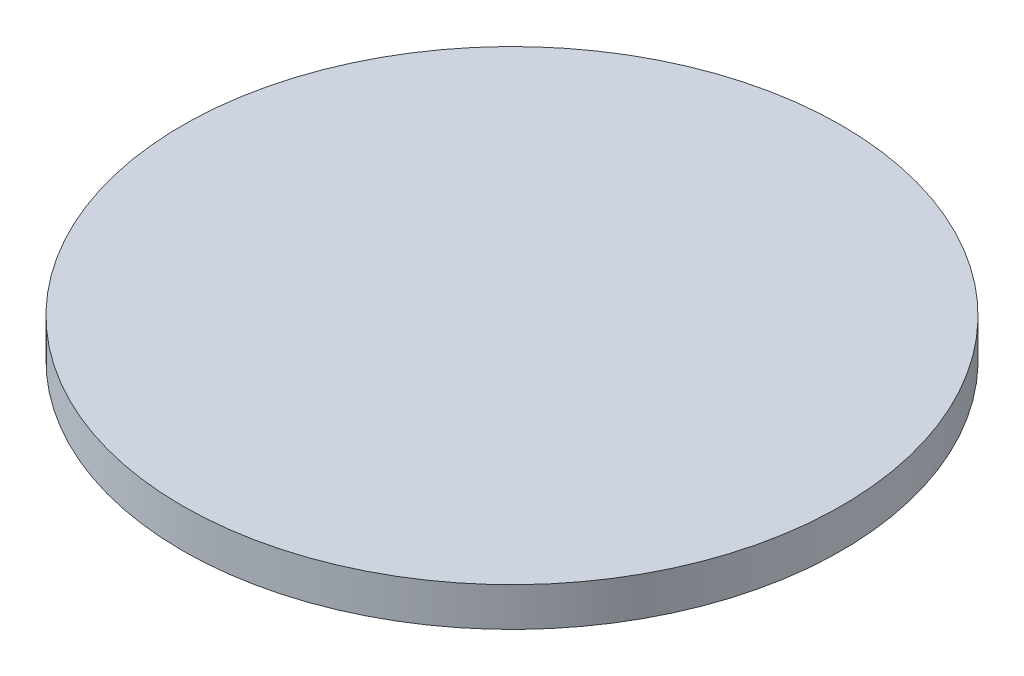
SolidWorks part; units mm, degrees
ref_plane "Alzado" through (0, 0, 0) normal (0, 0, 1) x (1, 0, 0)
ref_plane "Planta" through (0, 0, 0) normal (0, 1, 0) x (1, 0, 0)
ref_plane "Vista lateral" through (0, 0, 0) normal (1, 0, 0) x (0, 0, -1)
sketch "Croquis2" plane through (0, 0, 0) normal (0, 1, 0) x (1, 0, 0)
  circle A0 centre (0, 0) radius 85
  dimension "D1" = 170
extrude "Extruir2" add sketch "Croquis2" along normal blind 10
